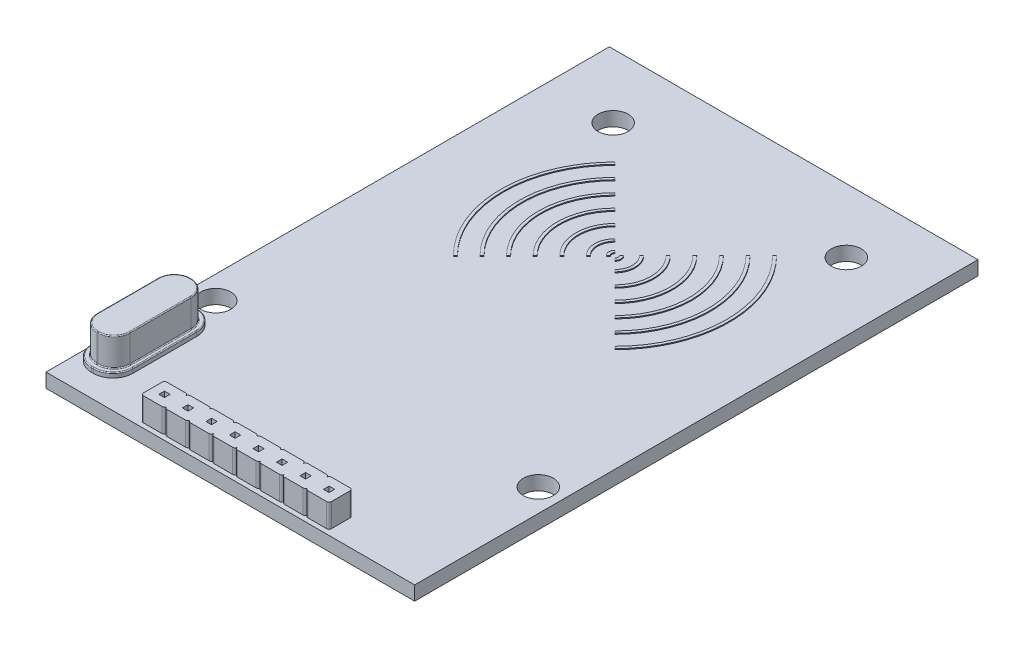
SolidWorks part; units mm, degrees
ref_plane "Front Plane" through (0, 0, 0) normal (0, 0, 1) x (1, 0, 0)
ref_plane "Top Plane" through (0, 0, 0) normal (0, 1, 0) x (1, 0, 0)
ref_plane "Right Plane" through (0, 0, 0) normal (1, 0, 0) x (0, 0, -1)
sketch "Sketch1" plane through (0, 0, 0) normal (0, 1, 0) x (1, 0, 0)
  line L1 (-19.6, 29.95) -> (19.6, 29.95)
  line L2 (-19.6, 29.95) -> (-19.6, -29.95)
  line L3 (-19.6, -29.95) -> (19.6, -29.95)
  line L4 (19.6, 29.95) -> (19.6, -29.95)
  line L5 (-19.6, 29.95) -> (19.6, -29.95) construction
  line L6 (-19.6, -29.95) -> (19.6, 29.95) construction
  point P0 (0, 0)
  dimension "D1" = 39.2
  dimension "D2" = 59.9
extrude "Boss-Extrude1" add sketch "Sketch1" along normal blind 1.5
sketch "Sketch3" plane through (0, 1.5, 0) normal (0, 1, 0) x (1, 0, 0)
  line L1 (-19.6, 29.95) -> (-19.6, -29.95) construction
  line L2 (19.6, 29.95) -> (-19.6, 29.95) construction
  line L5 (-19.6, -29.95) -> (19.6, -29.95) construction
  circle A0 centre (12.4, 23.15) radius 1.6
  circle A1 centre (-12.4, 23.15) radius 1.6
  circle A2 centre (17.15, -14.35) radius 1.6
  circle A3 centre (-17.15, -14.35) radius 1.6
  dimension "D1" = 3.2
  dimension "D2" = 24.8
  dimension "D3" = 6.8
  dimension "D4" = 7.2
  dimension "D5" = 6.8
  dimension "D6" = 34.3
  dimension "D7" = 2.45
  dimension "D8" = 15.6
  dimension "D9" = 15.6
extrude "Cut-Extrude1" cut sketch "Sketch3" against normal up to surface (1.5 mm away) up to face at (0, 0, 0)
sketch "Sketch4" plane through (0, 1.5, 0) normal (0, 1, 0) x (1, 0, 0)
  line L0 (-19.6, -29.95) -> (19.6, -29.95) construction
  line L1 (-9.75, -26.95) -> (-7.75, -26.95)
  line L2 (-10, -27.2) -> (-10, -29.2)
  line L3 (-9.75, -29.45) -> (-7.75, -29.45)
  line L5 (-19.6, 29.95) -> (-19.6, -29.95) construction
  line L7 (-7.25, -29.45) -> (-5.25, -29.45)
  line L9 (-7.25, -26.95) -> (-5.25, -26.95)
  line L11 (-4.75, -29.45) -> (-2.75, -29.45)
  line L13 (-4.75, -26.95) -> (-2.75, -26.95)
  line L15 (-2.25, -29.45) -> (-0.25, -29.45)
  line L17 (-2.25, -26.95) -> (-0.25, -26.95)
  line L19 (0.25, -29.45) -> (2.25, -29.45)
  line L21 (0.25, -26.95) -> (2.25, -26.95)
  line L23 (2.75, -29.45) -> (4.75, -29.45)
  line L25 (2.75, -26.95) -> (4.75, -26.95)
  line L27 (5.25, -29.45) -> (7.25, -29.45)
  line L29 (5.25, -26.95) -> (7.25, -26.95)
  line L30 (10, -27.2) -> (10, -29.2)
  line L31 (7.75, -29.45) -> (9.75, -29.45)
  line L33 (7.75, -26.95) -> (9.75, -26.95)
  line L34 (-7.5, -27.2) -> (-7.5, -29.2) [skipped]
  line L35 (-5, -27.2) -> (-5, -29.2) [skipped]
  line L36 (-2.5, -27.2) -> (-2.5, -29.2) [skipped]
  line L37 (0, -27.2) -> (0, -29.2) [skipped]
  line L38 (2.5, -27.2) -> (2.5, -29.2) [skipped]
  line L39 (5, -27.2) -> (5, -29.2) [skipped]
  line L40 (7.5, -27.2) -> (7.5, -29.2) [skipped]
  arc A1 (-7.75, -26.95) -> (-7.5, -27.2) centre (-7.75, -27.2) cw
  arc A2 (-7.5, -29.2) -> (-7.75, -29.45) centre (-7.75, -29.2) cw
  arc A3 (-9.75, -29.45) -> (-10, -29.2) centre (-9.75, -29.2) cw
  arc A4 (-10, -27.2) -> (-9.75, -26.95) centre (-9.75, -27.2) cw
  arc A5 (-5, -29.2) -> (-5.25, -29.45) centre (-5.25, -29.2) cw
  arc A6 (-7.25, -29.45) -> (-7.5, -29.2) centre (-7.25, -29.2) cw
  arc A7 (-7.5, -27.2) -> (-7.25, -26.95) centre (-7.25, -27.2) cw
  arc A8 (-5.25, -26.95) -> (-5, -27.2) centre (-5.25, -27.2) cw
  arc A10 (-2.5, -29.2) -> (-2.75, -29.45) centre (-2.75, -29.2) cw
  arc A11 (-4.75, -29.45) -> (-5, -29.2) centre (-4.75, -29.2) cw
  arc A12 (-5, -27.2) -> (-4.75, -26.95) centre (-4.75, -27.2) cw
  arc A13 (-2.75, -26.95) -> (-2.5, -27.2) centre (-2.75, -27.2) cw
  arc A15 (0, -29.2) -> (-0.25, -29.45) centre (-0.25, -29.2) cw
  arc A16 (-2.25, -29.45) -> (-2.5, -29.2) centre (-2.25, -29.2) cw
  arc A17 (-2.5, -27.2) -> (-2.25, -26.95) centre (-2.25, -27.2) cw
  arc A18 (-0.25, -26.95) -> (0, -27.2) centre (-0.25, -27.2) cw
  arc A20 (2.5, -29.2) -> (2.25, -29.45) centre (2.25, -29.2) cw
  arc A21 (0.25, -29.45) -> (0, -29.2) centre (0.25, -29.2) cw
  arc A22 (0, -27.2) -> (0.25, -26.95) centre (0.25, -27.2) cw
  arc A23 (2.25, -26.95) -> (2.5, -27.2) centre (2.25, -27.2) cw
  arc A25 (5, -29.2) -> (4.75, -29.45) centre (4.75, -29.2) cw
  arc A26 (2.75, -29.45) -> (2.5, -29.2) centre (2.75, -29.2) cw
  arc A27 (2.5, -27.2) -> (2.75, -26.95) centre (2.75, -27.2) cw
  arc A28 (4.75, -26.95) -> (5, -27.2) centre (4.75, -27.2) cw
  arc A30 (7.5, -29.2) -> (7.25, -29.45) centre (7.25, -29.2) cw
  arc A31 (5.25, -29.45) -> (5, -29.2) centre (5.25, -29.2) cw
  arc A32 (5, -27.2) -> (5.25, -26.95) centre (5.25, -27.2) cw
  arc A33 (7.25, -26.95) -> (7.5, -27.2) centre (7.25, -27.2) cw
  arc A35 (10, -29.2) -> (9.75, -29.45) centre (9.75, -29.2) cw
  arc A36 (7.75, -29.45) -> (7.5, -29.2) centre (7.75, -29.2) cw
  arc A37 (7.5, -27.2) -> (7.75, -26.95) centre (7.75, -27.2) cw
  arc A38 (9.75, -26.95) -> (10, -27.2) centre (9.75, -27.2) cw
  point P12 (-7.5, -26.95)
  point P17 (-10, -29.45)
  point P20 (-10, -26.95)
  dimension "D7" = 0.25
  dimension "D1" = 2.5
  dimension "D2" = 2.5
  dimension "D3" = 0.5
  dimension "D4" = 9.6
  dimension "D8" = 8
extrude "Boss-Extrude3" add sketch "Sketch4" along normal blind 2.5
sketch "Sketch5" plane through (0, 4, 0) normal (0, 1, 0) x (1, 0, 0)
  line L2 (-7.75, -26.95) -> (-9.75, -26.95) construction
  line L3 (-9.05, -27.9) -> (-8.45, -27.9)
  line L4 (-9.05, -27.9) -> (-9.05, -28.5)
  line L5 (-9.05, -28.5) -> (-8.45, -28.5)
  line L6 (-8.45, -27.9) -> (-8.45, -28.5)
  line L7 (-10, -27.2) -> (-10, -29.2) construction
  line L8 (-6.55, -27.9) -> (-5.95, -27.9)
  line L9 (-5.95, -27.9) -> (-5.95, -28.5)
  line L10 (-6.55, -28.5) -> (-5.95, -28.5)
  line L11 (-6.55, -27.9) -> (-6.55, -28.5)
  line L12 (-4.05, -27.9) -> (-3.45, -27.9)
  line L13 (-3.45, -27.9) -> (-3.45, -28.5)
  line L14 (-4.05, -28.5) -> (-3.45, -28.5)
  line L15 (-4.05, -27.9) -> (-4.05, -28.5)
  line L16 (-1.55, -27.9) -> (-0.95, -27.9)
  line L17 (-0.95, -27.9) -> (-0.95, -28.5)
  line L18 (-1.55, -28.5) -> (-0.95, -28.5)
  line L19 (-1.55, -27.9) -> (-1.55, -28.5)
  line L20 (0.95, -27.9) -> (1.55, -27.9)
  line L21 (1.55, -27.9) -> (1.55, -28.5)
  line L22 (0.95, -28.5) -> (1.55, -28.5)
  line L23 (0.95, -27.9) -> (0.95, -28.5)
  line L24 (3.45, -27.9) -> (4.05, -27.9)
  line L25 (4.05, -27.9) -> (4.05, -28.5)
  line L26 (3.45, -28.5) -> (4.05, -28.5)
  line L27 (3.45, -27.9) -> (3.45, -28.5)
  line L28 (5.95, -27.9) -> (6.55, -27.9)
  line L29 (6.55, -27.9) -> (6.55, -28.5)
  line L30 (5.95, -28.5) -> (6.55, -28.5)
  line L31 (5.95, -27.9) -> (5.95, -28.5)
  line L32 (8.45, -27.9) -> (9.05, -27.9)
  line L33 (9.05, -27.9) -> (9.05, -28.5)
  line L34 (8.45, -28.5) -> (9.05, -28.5)
  line L35 (8.45, -27.9) -> (8.45, -28.5)
  dimension "D1" = 0.6
  dimension "D2" = 0.6
  dimension "D3" = 0.95
  dimension "D4" = 0.95
  dimension "D5" = 8
extrude "Cut-Extrude2" cut sketch "Sketch5" against normal up to surface (4 mm away) up to face at (-17.15, 0, 15.95)
ref_plane "Plane1" through (0, -1, 0) normal (0, -1, 0) x (-1, 0, 0)
sketch "Sketch6" plane through (0, -1, 0) normal (0, -1, 0) x (-1, 0, 0)
  line L0 (6.55, -28.5) -> (5.95, -28.5)
  line L1 (9.05, -28.5) -> (8.45, -28.5)
  line L2 (9.05, -28.5) -> (9.05, -27.9)
  line L3 (9.05, -27.9) -> (8.45, -27.9)
  line L4 (8.45, -28.5) -> (8.45, -27.9)
  line L5 (5.95, -28.5) -> (5.95, -27.9)
  line L6 (6.55, -27.9) -> (5.95, -27.9)
  line L7 (6.55, -28.5) -> (6.55, -27.9)
  line L8 (4.05, -28.5) -> (3.45, -28.5)
  line L9 (3.45, -28.5) -> (3.45, -27.9)
  line L10 (4.05, -27.9) -> (3.45, -27.9)
  line L11 (4.05, -28.5) -> (4.05, -27.9)
  line L12 (1.55, -28.5) -> (0.95, -28.5)
  line L13 (0.95, -28.5) -> (0.95, -27.9)
  line L14 (1.55, -27.9) -> (0.95, -27.9)
  line L15 (1.55, -28.5) -> (1.55, -27.9)
  line L16 (-0.95, -28.5) -> (-1.55, -28.5)
  line L17 (-1.55, -28.5) -> (-1.55, -27.9)
  line L18 (-0.95, -27.9) -> (-1.55, -27.9)
  line L19 (-0.95, -28.5) -> (-0.95, -27.9)
  line L20 (-3.45, -28.5) -> (-4.05, -28.5)
  line L21 (-4.05, -28.5) -> (-4.05, -27.9)
  line L22 (-3.45, -27.9) -> (-4.05, -27.9)
  line L23 (-3.45, -28.5) -> (-3.45, -27.9)
  line L24 (-5.95, -28.5) -> (-6.55, -28.5)
  line L25 (-6.55, -28.5) -> (-6.55, -27.9)
  line L26 (-5.95, -27.9) -> (-6.55, -27.9)
  line L27 (-5.95, -28.5) -> (-5.95, -27.9)
  line L28 (-8.45, -28.5) -> (-9.05, -28.5)
  line L29 (-9.05, -28.5) -> (-9.05, -27.9)
  line L30 (-8.45, -27.9) -> (-9.05, -27.9)
  line L31 (-8.45, -28.5) -> (-8.45, -27.9)
  dimension "D1" = 8
sketch "Sketch8" plane through (0, 1.5, 0) normal (0, 1, 0) x (1, 0, 0)
  line L0 (-19.6, -29.95) -> (19.6, -29.95) construction
  line L1 (-17.16, -16.55) -> (-16.96, -16.55)
  line L2 (-19.26, -18.65) -> (-19.26, -25.45)
  line L3 (-17.16, -27.55) -> (-16.96, -27.55)
  line L4 (-14.86, -18.65) -> (-14.86, -25.45)
  arc A0 (-19.26, -25.45) -> (-17.16, -27.55) centre (-17.16, -25.45) ccw
  arc A1 (-16.96, -27.55) -> (-14.86, -25.45) centre (-16.96, -25.45) ccw
  arc A2 (-16.96, -16.55) -> (-14.86, -18.65) centre (-16.96, -18.65) cw
  arc A3 (-17.16, -16.55) -> (-19.26, -18.65) centre (-17.16, -18.65) ccw
  point P6 (-19.26, -27.55)
  point P11 (-14.86, -16.55)
  point P14 (-19.26, -16.55)
  dimension "D3" = 2.1
  dimension "D1" = 11
  dimension "D2" = 4.4
  dimension "D4" = 2.4
extrude "Boss-Extrude4" add sketch "Sketch8" along normal blind 0.5
sketch "Sketch10" plane through (0, 2, 0) normal (0, 1, 0) x (1, 0, 0)
  line L0 (-17.06, -16.55) -> (-17.06, -27.55) construction
  line L1 (-16.96, -16.55) -> (-17.16, -16.55) construction
  line L2 (-17.16, -27.55) -> (-16.96, -27.55) construction
  line L3 (-19.26, -22.05) -> (-14.86, -22.05) construction
  line L4 (-19.26, -18.65) -> (-19.26, -25.45) construction
  line L5 (-14.86, -25.45) -> (-14.86, -18.65) construction
  line L7 (-17.11, -17.1) -> (-17.01, -17.1)
  line L8 (-18.81, -18.8) -> (-18.81, -25.3)
  line L9 (-17.11, -27) -> (-17.01, -27)
  line L10 (-15.31, -18.8) -> (-15.31, -25.3)
  line L11 (-18.81, -17.1) -> (-15.31, -27) construction
  line L12 (-18.81, -27) -> (-15.31, -17.1) construction
  arc A0 (-18.81, -25.3) -> (-17.11, -27) centre (-17.11, -25.3) ccw
  arc A1 (-17.01, -27) -> (-15.31, -25.3) centre (-17.01, -25.3) ccw
  arc A2 (-15.31, -18.8) -> (-17.01, -17.1) centre (-17.01, -18.8) ccw
  arc A3 (-17.11, -17.1) -> (-18.81, -18.8) centre (-17.11, -18.8) ccw
  point P12 (-17.06, -22.05)
  dimension "D3" = 1.7
  dimension "D1" = 3.5
  dimension "D2" = 9.9
extrude "Boss-Extrude5" add sketch "Sketch10" along normal blind 3
fillet "Fillet1" radius 0.1 24 edges at (-18.3121, 5, 17.5979) (-17.06, 5, 17.1) (-15.8079, 5, 17.5979) (-15.31, 5, 22.05) (-15.8079, 5, 26.5021) (-17.06, 5, 27) (-18.3121, 5, 26.5021) (-18.3121, 2, 17.5979) (-17.06, 2, 17.1) (-15.8079, 2, 17.5979) (-15.31, 2, 22.05) (-15.8079, 2, 26.5021) (-17.06, 2, 27) (-18.3121, 2, 26.5021) (-18.6449, 2, 17.1651) (-17.06, 2, 16.55) (-15.4751, 2, 17.1651) (-14.86, 2, 22.05) (-15.4751, 2, 26.9349) (-17.06, 2, 27.55) (-18.6449, 2, 26.9349) (-18.81, 5, 22.05) (-18.81, 2, 22.05) (-19.26, 2, 22.05)
sketch "Sketch11" plane through (0, 1.5, 0) normal (0, 1, 0) x (1, 0, 0)
  line L0 (-0.2475, 11.1975) -> (-0.4596, 11.4096)
  line L1 (-0.35, 10.95) -> (-19.6, 10.95) construction
  line L2 (-19.6, 29.95) -> (-19.6, -29.95) construction
  line L3 (19.6, 29.95) -> (-19.6, 29.95) construction
  line L4 (0.2475, 11.1975) -> (0.4596, 11.4096)
  line L5 (-0.2475, 10.7025) -> (-0.4596, 10.4904)
  line L6 (0.2475, 10.7025) -> (0.4596, 10.4904)
  line L7 (-8.4853, 19.4353) -> (-8.5913, 19.5413)
  line L8 (-8.5913, 2.3587) -> (-8.4853, 2.4647)
  line L9 (8.4853, 2.4647) -> (8.5913, 2.3587)
  line L10 (8.4853, 19.4353) -> (8.5913, 19.5413)
  line L11 (-8.3792, 19.3292) -> (-8.4853, 19.4353)
  line L12 (-6.965, 17.915) -> (-7.1771, 18.1271)
  line L13 (-5.5508, 16.5008) -> (-5.7629, 16.7129)
  line L14 (-4.1366, 15.0866) -> (-4.3487, 15.2987)
  line L15 (-2.7224, 13.6724) -> (-2.9345, 13.8845)
  line L16 (-1.3081, 12.2581) -> (-1.5203, 12.4703)
  line L17 (-1.3081, 9.6419) -> (-1.5203, 9.4297)
  line L18 (-2.7224, 8.2276) -> (-2.9345, 8.0155)
  line L19 (-4.1366, 6.8134) -> (-4.3487, 6.6013)
  line L20 (-5.5508, 5.3992) -> (-5.7629, 5.1871)
  line L21 (-8.3792, 2.5708) -> (-8.4853, 2.4647)
  line L22 (1.3081, 9.6419) -> (1.5203, 9.4297)
  line L23 (2.7224, 8.2276) -> (2.9345, 8.0155)
  line L24 (4.1366, 6.8134) -> (4.3487, 6.6013)
  line L25 (5.5508, 5.3992) -> (5.7629, 5.1871)
  line L26 (6.965, 3.985) -> (7.1771, 3.7729)
  line L27 (8.3792, 2.5708) -> (8.4853, 2.4647)
  line L28 (1.3081, 12.2581) -> (1.5203, 12.4703)
  line L29 (2.7224, 13.6724) -> (2.9345, 13.8845)
  line L30 (4.1366, 15.0866) -> (4.3487, 15.2987)
  line L31 (5.5508, 16.5008) -> (5.7629, 16.7129)
  line L32 (6.965, 17.915) -> (7.1771, 18.1271)
  line L33 (8.3792, 19.3292) -> (8.4853, 19.4353)
  line L34 (-6.965, 3.985) -> (-7.1771, 3.7729)
  arc A0 (-0.3536, 11.3036) -> (-0.3536, 10.5964) centre (0, 10.95) ccw construction
  arc A1 (-1.4142, 12.3642) -> (-1.4142, 9.5358) centre (0, 10.95) ccw construction
  arc A2 (-2.8284, 13.7784) -> (-2.8284, 8.1216) centre (0, 10.95) ccw construction
  arc A3 (-4.2426, 15.1926) -> (-4.2426, 6.7074) centre (0, 10.95) ccw construction
  arc A4 (-5.6569, 16.6069) -> (-5.6569, 5.2931) centre (0, 10.95) ccw construction
  arc A5 (-5.6569, 16.6069) -> (-5.6569, 5.2931) centre (0, 10.95) ccw
  arc A6 (-7.0711, 18.0211) -> (-7.0711, 3.8789) centre (0, 10.95) ccw construction
  arc A7 (-8.4853, 19.4353) -> (-8.4853, 2.4647) centre (0, 10.95) ccw construction
  arc A8 (0.3536, 10.5964) -> (0.3536, 11.3036) centre (0, 10.95) ccw construction
  arc A9 (1.4142, 9.5358) -> (1.4142, 12.3642) centre (0, 10.95) ccw construction
  arc A10 (2.8284, 8.1216) -> (2.8284, 13.7784) centre (0, 10.95) ccw construction
  arc A11 (4.2426, 6.7074) -> (4.2426, 15.1926) centre (0, 10.95) ccw construction
  arc A12 (5.6569, 5.2931) -> (5.6569, 16.6069) centre (0, 10.95) ccw construction
  arc A13 (5.6569, 5.2931) -> (5.6569, 16.6069) centre (0, 10.95) ccw
  arc A14 (7.0711, 3.8789) -> (7.0711, 18.0211) centre (0, 10.95) ccw construction
  arc A15 (8.4853, 2.4647) -> (8.4853, 19.4353) centre (0, 10.95) ccw construction
  arc A16 (-8.5913, 19.5413) -> (-8.5913, 2.3587) centre (0, 10.95) ccw
  arc A17 (-7.1771, 18.1271) -> (-7.1771, 3.7729) centre (0, 10.95) ccw
  arc A18 (-5.7629, 16.7129) -> (-5.7629, 5.1871) centre (0, 10.95) ccw
  arc A19 (-4.3487, 15.2987) -> (-4.3487, 6.6013) centre (0, 10.95) ccw
  arc A20 (-2.9345, 13.8845) -> (-2.9345, 8.0155) centre (0, 10.95) ccw
  arc A21 (-1.5203, 12.4703) -> (-1.5203, 9.4297) centre (0, 10.95) ccw
  arc A22 (-0.4596, 11.4096) -> (-0.4596, 10.4904) centre (0, 10.95) ccw
  arc A23 (0.4596, 10.4904) -> (0.4596, 11.4096) centre (0, 10.95) ccw
  arc A24 (1.5203, 9.4297) -> (1.5203, 12.4703) centre (0, 10.95) ccw
  arc A25 (2.9345, 8.0155) -> (2.9345, 13.8845) centre (0, 10.95) ccw
  arc A26 (4.3487, 6.6013) -> (4.3487, 15.2987) centre (0, 10.95) ccw
  arc A27 (5.7629, 5.1871) -> (5.7629, 16.7129) centre (0, 10.95) ccw
  arc A28 (7.1771, 3.7729) -> (7.1771, 18.1271) centre (0, 10.95) ccw
  arc A29 (8.5913, 2.3587) -> (8.5913, 19.5413) centre (0, 10.95) ccw
  arc A30 (-8.3792, 19.3292) -> (-8.3792, 2.5708) centre (0, 10.95) ccw
  arc A31 (-6.965, 17.915) -> (-6.965, 3.985) centre (0, 10.95) ccw
  arc A32 (-5.5508, 16.5008) -> (-5.5508, 5.3992) centre (0, 10.95) ccw
  arc A33 (-4.1366, 15.0866) -> (-4.1366, 6.8134) centre (0, 10.95) ccw
  arc A34 (-2.7224, 13.6724) -> (-2.7224, 8.2276) centre (0, 10.95) ccw
  arc A35 (-1.3081, 12.2581) -> (-1.3081, 9.6419) centre (0, 10.95) ccw
  arc A36 (-0.2475, 11.1975) -> (-0.2475, 10.7025) centre (0, 10.95) ccw
  arc A37 (0.2475, 10.7025) -> (0.2475, 11.1975) centre (0, 10.95) ccw
  arc A38 (1.3081, 9.6419) -> (1.3081, 12.2581) centre (0, 10.95) ccw
  arc A39 (2.7224, 8.2276) -> (2.7224, 13.6724) centre (0, 10.95) ccw
  arc A40 (4.1366, 6.8134) -> (4.1366, 15.0866) centre (0, 10.95) ccw
  arc A41 (5.5508, 5.3992) -> (5.5508, 16.5008) centre (0, 10.95) ccw
  arc A42 (6.965, 3.985) -> (6.965, 17.915) centre (0, 10.95) ccw
  arc A43 (8.3792, 2.5708) -> (8.3792, 19.3292) centre (0, 10.95) ccw
  dimension "D1" = 45
  dimension "D2" = 0.5
  dimension "D3" = 2
  dimension "D4" = 6
  dimension "D5" = 10
  dimension "D6" = 19
  dimension "D10" = 8
  dimension "D11" = 4
  dimension "D12" = 12
  dimension "D7" = 45
  dimension "D8" = 45
  dimension "D9" = 45
  dimension "D13" = 0.15
  dimension "D14" = 0.15
extrude "Boss-Extrude6" add sketch "Sketch11" along normal blind 0.1 contours A16 L8 L21 A30 L11 L7 | A17 L34 A31 L12 | A18 L20 A32 L13 | A19 L19 A33 L14 | A20 L18 A34 L15 | A35 L17 A21 L16 | A36 L5 A22 L0 | A23 L4 A37 L6 | A24 L28 A38 L22 | A25 L29 A39 L23 | A26 L30 A40 L24 | A27 L31 A41 L25 | A28 L32 A42 L26 | A29 L10 L33 A43 L27 L9
